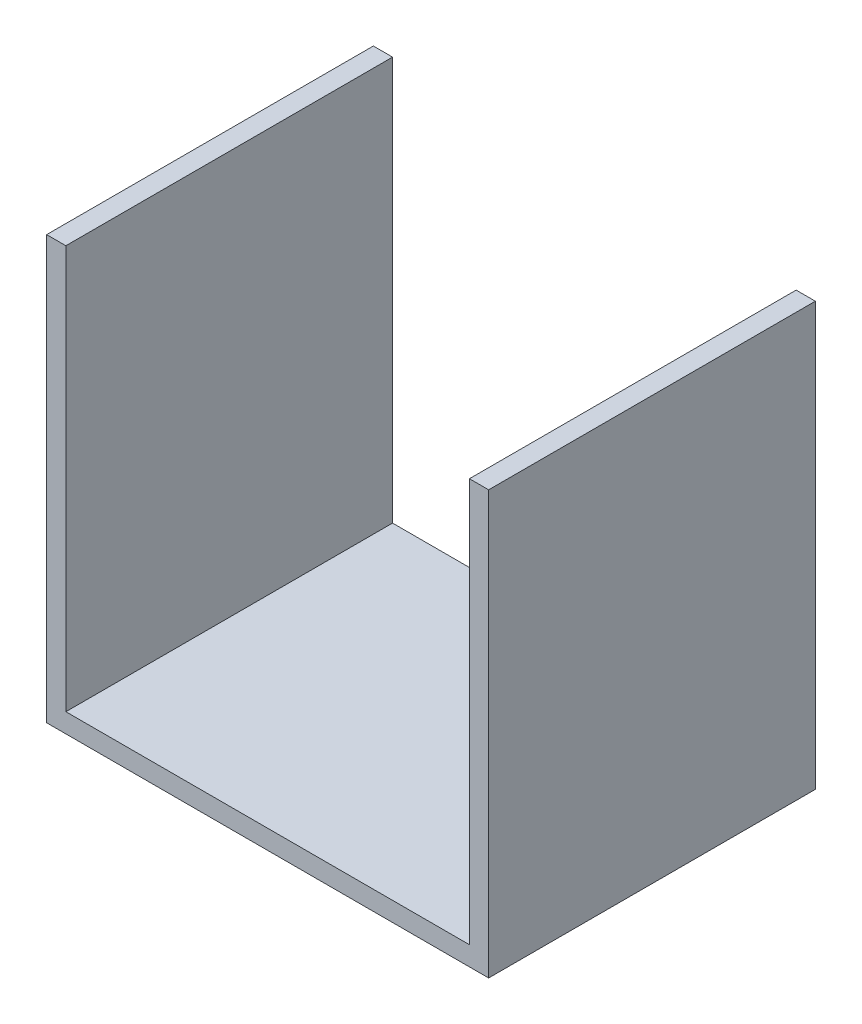
SolidWorks part; units mm, degrees
ref_plane "前视基准面" through (0, 0, 0) normal (0, 0, 1) x (1, 0, 0)
ref_plane "上视基准面" through (0, 0, 0) normal (0, 1, 0) x (1, 0, 0)
ref_plane "右视基准面" through (0, 0, 0) normal (1, 0, 0) x (0, 0, -1)
other "Configuration Table"
sketch "草图1" plane through (0, 0, 0) normal (0, 0, 1) x (1, 0, 0)
  line L0 (0, 42) -> (-2, 42)
  line L1 (0, 0) -> (42, 0)
  line L2 (0, 0) -> (0, 42)
  line L4 (42, 0) -> (42, 42)
  line L5 (-2, 42) -> (-2, -2)
  line L6 (-2, -2) -> (44, -2)
  line L7 (44, -2) -> (44, 42)
  line L8 (44, 42) -> (42, 42)
  dimension "D1" = 42
  dimension "D2" = 42
  dimension "D3" = 2
  dimension "D4" = 2
  dimension "D5" = 2
extrude "凸台-拉伸1" add sketch "草图1" along normal blind 34
